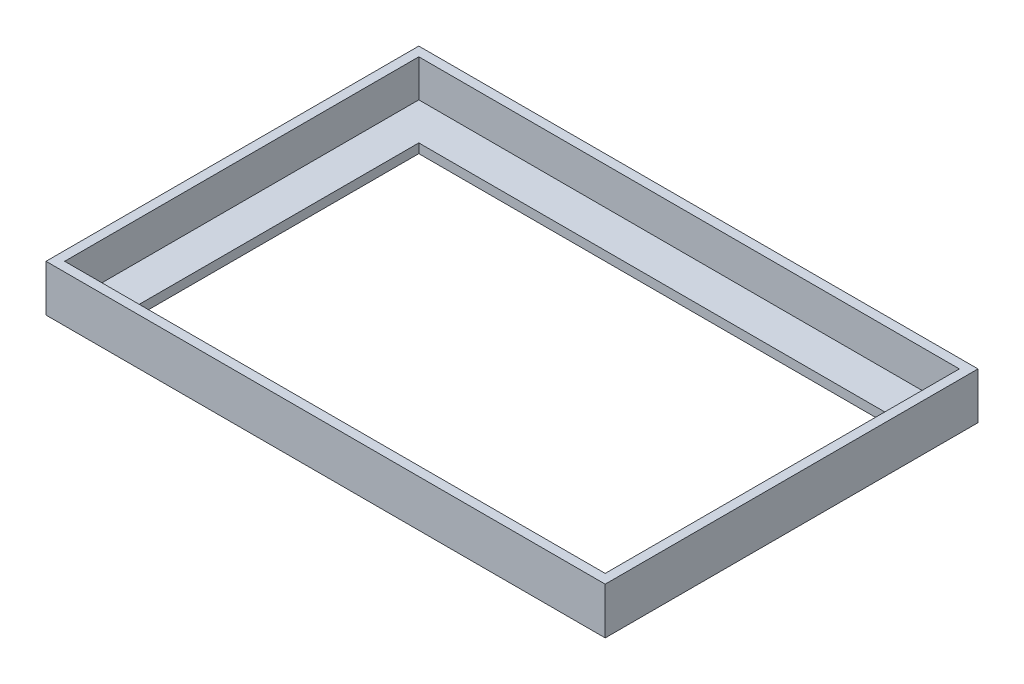
SolidWorks part; units mm, degrees
ref_plane "Front Plane" through (0, 0, 0) normal (0, 0, 1) x (1, 0, 0)
ref_plane "Top Plane" through (0, 0, 0) normal (0, 1, 0) x (1, 0, 0)
ref_plane "Right Plane" through (0, 0, 0) normal (1, 0, 0) x (0, 0, -1)
sketch "Sketch3" plane through (0, 0, 0) normal (0, 1, 0) x (1, 0, 0)
  line L1 (0, 0) -> (60, 0)
  line L2 (0, 0) -> (0, 40)
  line L3 (0, 40) -> (60, 40)
  line L4 (60, 0) -> (60, 40)
  dimension "D1" = 40
  dimension "D2" = 60
extrude "Boss-Extrude1" add sketch "Sketch3" along normal blind 5
sketch "Sketch6" plane through (0, 0, 0) normal (0, 1, 0) x (1, 0, 0)
  line L0 (0, 40) -> (0, 0) construction
  line L1 (1, 39) -> (59, 39)
  line L2 (1, 39) -> (1, 1)
  line L3 (1, 1) -> (59, 1)
  line L4 (59, 39) -> (59, 1)
  line L5 (0, 0) -> (60, 0) construction
  dimension "D1" = 38
  dimension "D2" = 58
  dimension "D3" = 1
  dimension "D4" = 1
extrude "Cut-Extrude1" cut sketch "Sketch6" along normal through all both and the other way through all contours L2 L1 L4 L3
sketch "Sketch7" plane through (0, 0, 0) normal (0, 1, 0) x (1, 0, 0)
  line L1 (60, 40) -> (0, 40)
  line L2 (60, 40) -> (60, 0)
  line L3 (60, 0) -> (0, 0)
  line L4 (0, 40) -> (0, 0)
extrude "Boss-Extrude2" add sketch "Sketch7" along normal blind 1
sketch "Sketch8" plane through (0, 0, 0) normal (0, -1, 0) x (1, 0, 0)
  line L0 (0, -40) -> (0, 0) construction
  line L1 (5, -5) -> (55, -5)
  line L2 (5, -5) -> (5, -35)
  line L3 (5, -35) -> (55, -35)
  line L4 (55, -5) -> (55, -35)
  line L5 (60, -40) -> (0, -40) construction
  dimension "D1" = 30
  dimension "D2" = 50
  dimension "D3" = 5
  dimension "D4" = 5
extrude "Cut-Extrude2" cut sketch "Sketch8" against normal through all both and the other way through all
